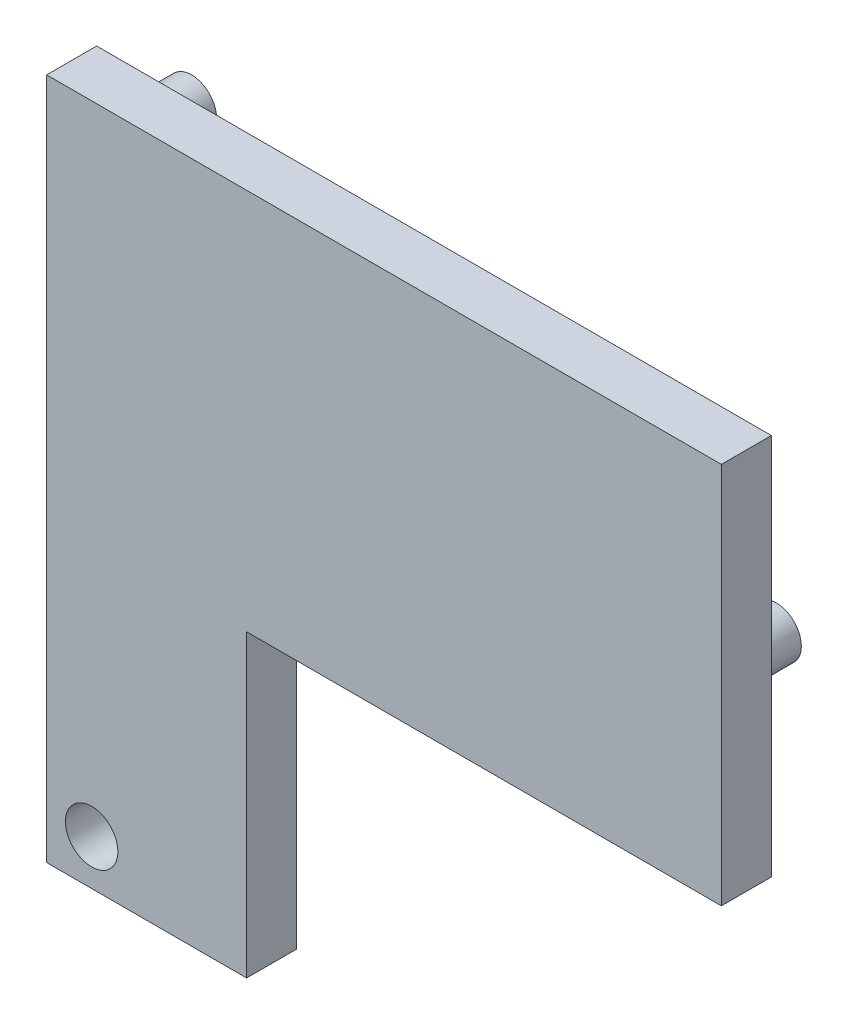
SolidWorks part; units mm, degrees
ref_plane "Front Plane" through (0, 0, 0) normal (0, 0, 1) x (1, 0, 0)
ref_plane "Top Plane" through (0, 0, 0) normal (0, 1, 0) x (1, 0, 0)
ref_plane "Right Plane" through (0, 0, 0) normal (1, 0, 0) x (0, 0, -1)
sketch "Sketch1" plane through (0, 0, 0) normal (0, 0, 1) x (1, 0, 0)
  line L0 (-51.85, -32.1) -> (-51.85, -55.5) construction
  line L1 (-51.85, -55.5) -> (-51.85, -57.3) construction
  line L2 (-51.85, -57.3) -> (-53.65, -57.3) construction
  line L3 (-50.65, -30) -> (-26.15, -30) construction
  line L4 (-53.65, -57.3) -> (-45.65, -57.3)
  line L5 (-53.65, -57.3) -> (-53.65, -30)
  line L6 (-53.65, -30) -> (-26.65, -30)
  line L7 (-26.65, -45.3) -> (-26.65, -30)
  line L8 (-53.65, -57.3) -> (-45.65, -57.3) construction
  line L9 (-45.65, -57.3) -> (-45.65, -45.3)
  line L10 (-45.65, -45.3) -> (-26.65, -45.3)
  circle A2 centre (-51.85, -55.5) radius 1.05
  dimension "D7" = 2.1
  dimension "D1" = 23.4
  dimension "D2" = 1.8
  dimension "D3" = 1.8
  dimension "D4" = 27
  dimension "D8" = 8
  dimension "D9" = 12
extrude "Boss-Extrude1" add sketch "Sketch1" along normal blind 2
sketch "Sketch2" plane through (0, 0, 2) normal (0, 0, 1) x (1, 0, 0)
  circle A0 centre (-28.45, -38.7) radius 1
  circle A1 centre (-51.85, -32.1) radius 1
  dimension "D1" = 2
  dimension "D2" = 2
extrude "Boss-Extrude2" add sketch "Sketch2" against normal blind 4
